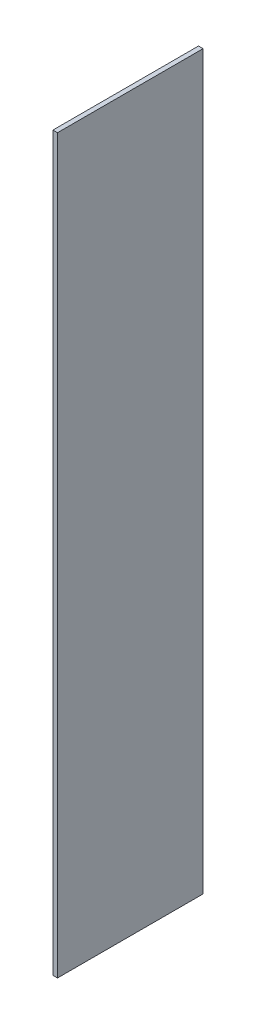
SolidWorks part; units mm, degrees
ref_plane "Top" through (0, 0, 0) normal (0, 0, 1) x (1, 0, 0)
ref_plane "Front" through (0, 0, 0) normal (0, 1, 0) x (1, 0, 0)
ref_plane "Right" through (0, 0, 0) normal (1, 0, 0) x (0, 0, -1)
sketch "Profile Sketch" plane through (0.0456, 0, -0.0242) normal (0, 1, 0) x (-1, 0, 0)
  line L0 (0.5956, -17.4758) -> (0.5956, 0.0242)
  line L1 (0.5956, 0.0242) -> (0.0456, 0.0242)
  line L2 (0.0456, 0.0242) -> (0.0456, -17.4758)
  line L3 (0.0456, -17.4758) -> (0.5956, -17.4758)
  dimension "D1" = 17.5
  dimension "D2" = 0.55
extrude "Profile Extrude" add sketch "Profile Sketch" along normal blind 88
ref_plane "Mid Plane" through (0, 44, 0) normal (0, -1, 0) x (-1, 0, 0)
